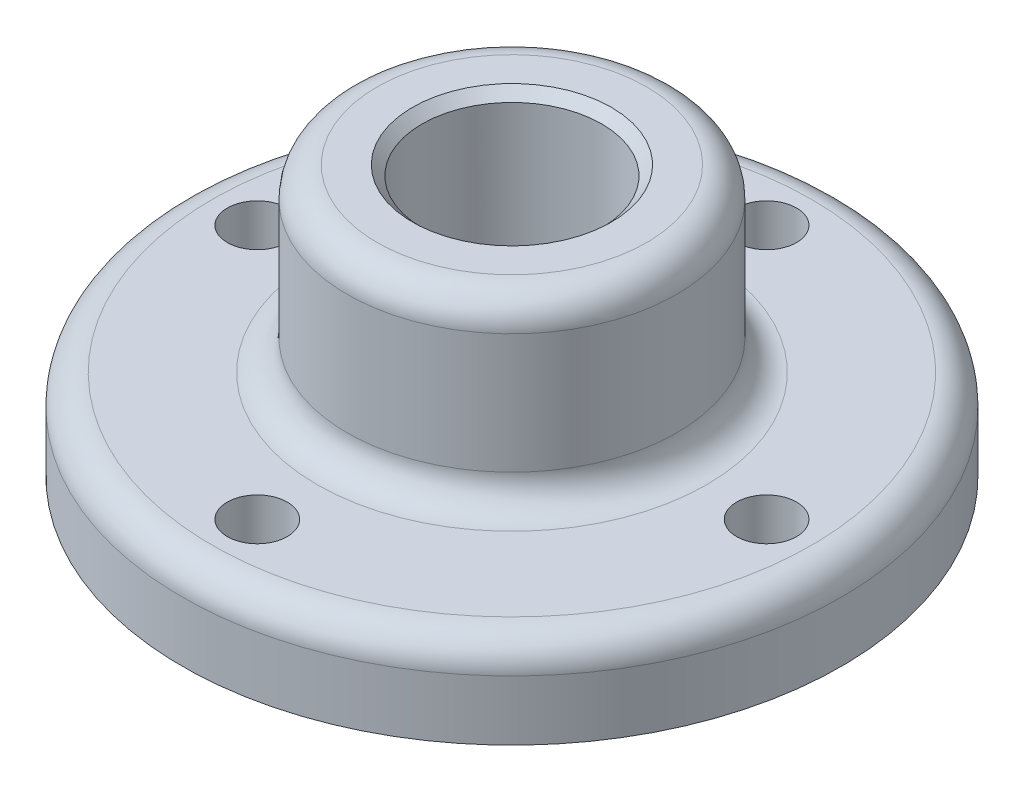
SolidWorks part; units mm, degrees
ref_plane "Front Plane" through (0, 0, 0) normal (0, 0, 1) x (1, 0, 0)
ref_plane "Top Plane" through (0, 0, 0) normal (0, 1, 0) x (1, 0, 0)
ref_plane "Right Plane" through (0, 0, 0) normal (1, 0, 0) x (0, 0, -1)
sketch "Sketch7" plane through (0, 0, 0) normal (0, 0, 1) x (1, 0, 0)
  line L0 (0, 0) -> (0, 101.7639) construction
  line L1 (34.925, 0) -> (69.85, 0)
  line L2 (0, 0) -> (0, -19.05)
  line L3 (0, -19.05) -> (69.85, -19.05)
  line L4 (69.85, 0) -> (69.85, -19.05)
  line L5 (0, 38.1) -> (34.925, 38.1)
  line L6 (0, 38.1) -> (0, 0)
  line L8 (34.925, 38.1) -> (34.925, 0)
  line L9 (0, 0) -> (106.9258, 0) construction
  dimension "Boss Diameter" = 69.85
revolve "Revolve1" add sketch "Sketch7" angle 360 about L6
sketch "Sketch8" plane through (0, 38.1, 0) normal (0, 1, 0) x (1, 0, 0)
  circle A0 centre (0, 0) radius 19.05
  dimension "Center Hole Diameter" = 38.1
extrude "Cut-Extrude2" cut sketch "Sketch8" against normal through all
sketch "Sketch9" plane through (0, 0, 0) normal (0, 1, 0) x (1, 0, 0)
  line L0 (0, 0) -> (0, 56.8912) construction
  circle A0 centre (0, 0) radius 53.975 construction
  circle A1 centre (0, 53.975) radius 6.35
  point P15 (0, 0)
extrude "Cut-Extrude3" cut sketch "Sketch9" against normal through all
pattern_circular "CirPattern1" count 4 over 360 about axis through (0, 0, 0) along (0, 1, 0) of "Cut-Extrude3"
fillet "Fillet1" radius 6.35 3 edges at (0, 0, -34.925) (0, 0, -69.85) (0, 38.1, -34.925)
chamfer "Chamfer1" distance 2.032 angle 45 1 edges at (0, 38.1, 19.05)
equation "\"Boss Diameter@Sketch7\"= 1 / 2 * \"Base Diameter@Sketch7\""
equation "\"Center Hole Diameter@Sketch8\"= \"Boss Diameter@Sketch7\" - 1.25"
equation "\"Base Height@Sketch7\"=\"Total Height@Sketch7\" / 3"
equation "\"Bolt Circle Diameter@Sketch9\"=\"Base Diameter@Sketch7\" - 1.25"
